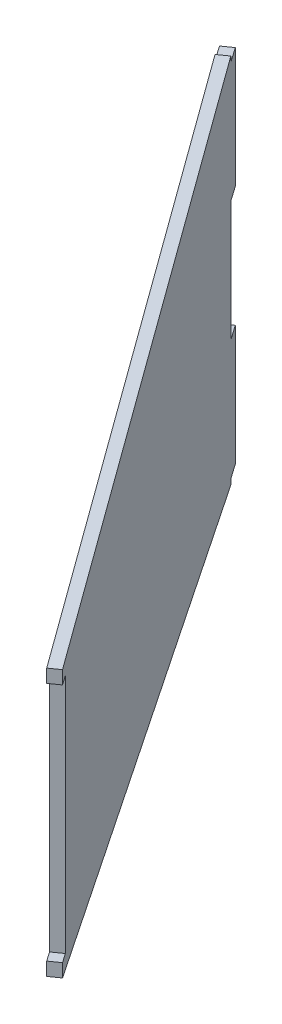
SolidWorks part; units mm, degrees
ref_plane "Front Plane" through (0, 0, 0) normal (0, 0, 1) x (1, 0, 0)
ref_plane "Top Plane" through (0, 0, 0) normal (0, 1, 0) x (1, 0, 0)
ref_plane "Right Plane" through (0, 0, 0) normal (1, 0, 0) x (0, 0, -1)
ref_plane "Plane1" through (5.1928, 0, -3.6413) normal (0.8188, 0, -0.5741) x (-0.5741, 0, -0.8188)
sketch "Sketch10" plane through (5.1928, 0, -3.6413) normal (0.8188, 0, -0.5741) x (-0.5741, 0, -0.8188)
  line L0 (-651.7496, -739.4253) -> (-8.6516, -690.6252)
  line L1 (-8.6516, -695.6252) -> (8.3484, -695.6252)
  line L3 (8.3484, -808.0249) -> (-8.6516, -808.0249)
  line L4 (-8.6516, -808.0249) -> (-8.6516, -920.4247)
  line L5 (-8.6516, -1032.8244) -> (-8.6516, -920.4247) construction
  line L6 (-8.6516, -920.4247) -> (1.1564, -920.4247) construction
  line L7 (-8.6516, -920.4247) -> (8.3484, -920.4247)
  line L9 (8.3484, -1032.8244) -> (-8.6516, -1032.8244)
  line L10 (-8.6516, -1032.8244) -> (-8.6516, -1037.8244)
  line L13 (-651.7496, -976.6245) -> (-641.1277, -976.6245)
  line L14 (-641.1277, -976.6245) -> (-641.1277, -751.825)
  line L16 (-651.7496, -751.825) -> (-641.1277, -751.825)
  line L17 (-8.6516, -695.6252) -> (-8.6516, -690.6252)
  line L18 (8.3484, -695.6252) -> (8.3484, -808.0249)
  line L20 (8.3484, -808.0249) -> (8.3484, -920.4247) construction
  line L21 (8.3484, -920.4247) -> (8.3484, -1032.8244)
  line L22 (-651.7496, -989.0243) -> (-8.6516, -1037.8244)
  line L23 (-651.7496, -751.825) -> (-651.7496, -739.4253) construction
  line L24 (-651.7496, -751.825) -> (-651.7496, -739.4253)
  line L25 (-651.7496, -989.0243) -> (-651.7496, -976.6245) construction
  line L26 (-651.7496, -989.0243) -> (-651.7496, -976.6245)
  dimension "D1" = 5
  dimension "D2" = 17
  dimension "D3" = 5
extrude "Boss-Extrude4" add sketch "Sketch10" against normal blind 10.6 separate body
